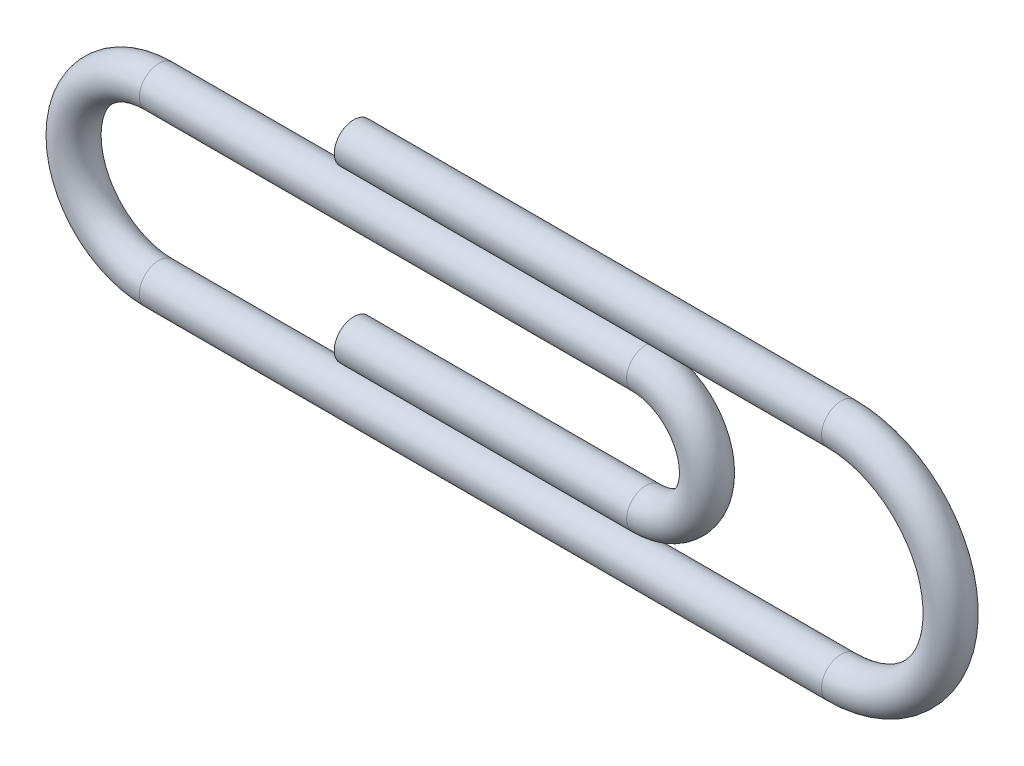
SolidWorks part; units mm, degrees
material "Сталь"
ref_plane "Спереди" through (0, 0, 0) normal (0, 0, 1) x (1, 0, 0)
ref_plane "Сверху" through (0, 0, 0) normal (0, 1, 0) x (1, 0, 0)
ref_plane "Справа" through (0, 0, 0) normal (1, 0, 0) x (0, 0, -1)
sketch "Эскиз1" plane through (0, 0, 0) normal (0, 0, 1) x (1, 0, 0)
  line L0 (0, 0) -> (60, 0) construction
  line L1 (0, 12.5) -> (60, 12.5) construction
  line L2 (0, -12.5) -> (60, -12.5) construction
  line L3 (-40, -5) -> (60, -5) construction
  line L4 (-40, 12.5) -> (60, 12.5) construction
  line L5 (-40, -22.5) -> (60, -22.5) construction
  line L6 (100, 0) -> (-40, 0) construction
  line L7 (100, -22.5) -> (-40, -22.5) construction
  line L8 (100, 22.5) -> (-40, 22.5) construction
  arc A0 (0, 12.5) -> (0, -12.5) centre (0, 0) ccw construction
  arc A1 (60, -12.5) -> (60, 12.5) centre (60, 0) ccw construction
  arc A2 (-40, 12.5) -> (-40, -22.5) centre (-40, -5) ccw construction
  arc A3 (60, -22.5) -> (60, 12.5) centre (60, -5) ccw construction
  arc A4 (100, -22.5) -> (100, 22.5) centre (100, 0) ccw construction
  arc A5 (-40, 22.5) -> (-40, -22.5) centre (-40, 0) ccw construction
  point P3 (30, 0)
  point P10 (10, -5)
  point P17 (30, 0)
  dimension "D1" = 25
  dimension "D2" = 60
  dimension "D3" = 35
  dimension "D4" = 100
  dimension "D5" = 45
  dimension "D6" = 140
sketch "Эскиз2" plane through (0, 0, 0) normal (0, 0, 1) x (1, 0, 0)
  line L0 (0, -12.5) -> (60, -12.5)
  line L1 (60, 12.5) -> (-40, 12.5)
  line L2 (-40, -22.5) -> (100, -22.5)
  line L3 (100, 22.5) -> (0, 22.5)
  line L4 (100, 22.5) -> (-40, 22.5) construction
  arc A0 (60, -12.5) -> (60, 12.5) centre (60, 0) ccw
  arc A1 (-40, 12.5) -> (-40, -22.5) centre (-40, -5) ccw
  arc A2 (100, -22.5) -> (100, 22.5) centre (100, 0) ccw
ref_plane "Плоскость1" through (0, 22.5, 0) normal (-1, 0, 0) x (0, 0, 1)
sketch "Эскиз3" plane through (0, 22.5, 0) normal (-1, 0, 0) x (0, 0, 1)
  line L1 (0, 2.8868) -> (-2.5, 1.4434)
  line L2 (-2.5, 1.4434) -> (-2.5, -1.4434)
  line L3 (-2.5, -1.4434) -> (0, -2.8868)
  line L4 (0, -2.8868) -> (2.5, -1.4434)
  line L5 (2.5, -1.4434) -> (2.5, 1.4434)
  line L6 (2.5, 1.4434) -> (0, 2.8868)
  circle A0 centre (0, 0) radius 4
  circle A1 centre (0, 0) radius 2.5 construction
  dimension "D1" = 8
  dimension "D2" = 5
sweep "По траектории2" add profiles "Эскиз3" path "Эскиз2"
